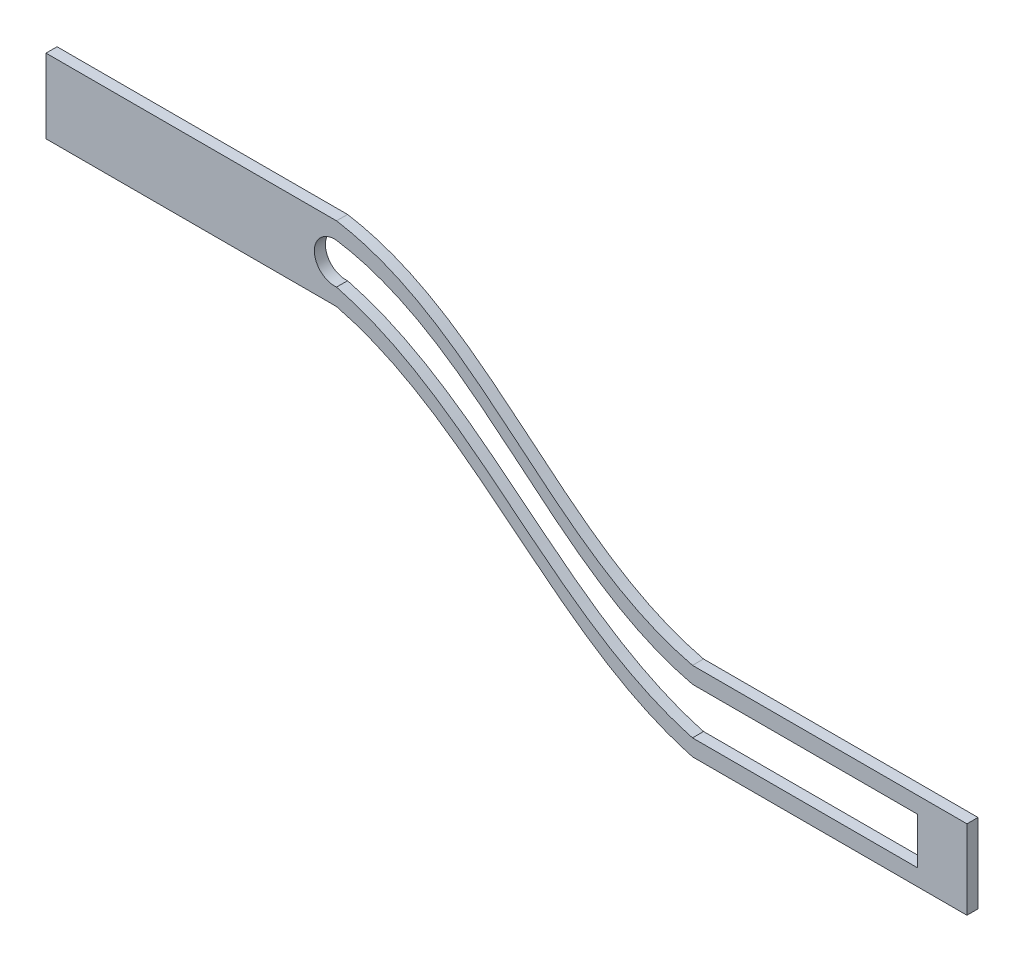
SolidWorks part; units mm, degrees
ref_plane "Front Plane" through (0, 0, 0) normal (0, 0, 1) x (1, 0, 0)
ref_plane "Top Plane" through (0, 0, 0) normal (0, 1, 0) x (1, 0, 0)
ref_plane "Right Plane" through (0, 0, 0) normal (1, 0, 0) x (0, 0, -1)
sketch "Sketch1" plane through (0, 0, 0) normal (0, 0, 1) x (1, 0, 0)
  line L0 (-253.4284, 58.4447) -> (-232.5525, 58.4447) construction
  line L1 (-89.9277, -13.6268) -> (-89.9277, 78.7653) construction
  line L2 (-183.4344, 71.2182) -> (-283.3881, 71.2182)
  line L3 (-183.4344, 45.6712) -> (-283.3881, 45.6712)
  line L4 (-283.3881, 45.6712) -> (-283.3881, 71.2182)
  line L5 (-183.4344, 65.4182) -> (-183.4344, 43.2992) construction
  line L6 (16.4159, -5.6454) -> (-60.9483, -5.6454)
  line L7 (-60.9483, -21.6083) -> (16.4159, -21.6083)
  line L8 (16.4159, -21.6083) -> (16.4159, -5.6454)
  line L14 (16.4159, -13.6268) -> (-13.7314, -13.6268) construction
  line L22 (-60.9483, -27.2537) -> (33.4855, -27.2537)
  line L23 (33.4855, -27.2537) -> (33.4855, 0)
  line L24 (33.4855, 0) -> (-60.9483, 0)
  circle A0 centre (16.4014, -13.6268) radius 4.5636 construction
  arc A1 (-183.4344, 65.4182) -> (-183.4344, 51.4712) centre (-184.0434, 58.4447) ccw
  spline S0 degree 3 poles (11.8418, -13.435) (-307.1508, 151.8659) (-138.2968, 25.2289) (-60.9483, -13.6268) knots 0 0 0 0 1 1 1 1 construction
  spline S1 degree 3 poles (-183.4344, 71.2182) (-134.5968, 63.242) (-109.1058, 11.4345) (-60.9483, 0) knots 0 0 0 0 1 1 1 1
  spline S2 degree 3 poles (-183.4344, 45.6712) (-135.8231, 33.7106) (-108.756, -14.3126) (-60.9483, -27.2537) knots 0 0 0 0 1 1 1 1
  spline S3 degree 3 poles (-183.4344, 65.4182) (-134.4942, 57.8131) (-109.1359, 5.6482) (-60.9483, -5.6454) knots 0 0 0 0 1 1 1 1
  spline S4 degree 3 poles (-183.4344, 51.4712) (-135.9421, 39.1601) (-108.723, -8.5354) (-60.9483, -21.6083) knots 0 0 0 0 1 1 1 1
  point P20 (-184.0814, 58.0092)
  point P24 (0, 0)
  point P25 (-183.4344, 51.4712)
  dimension "D1" = 5.8
  dimension "D3" = 14
  dimension "D2" = 5.8
extrude "Boss-Extrude1" add sketch "Sketch1" along normal blind 3.8
